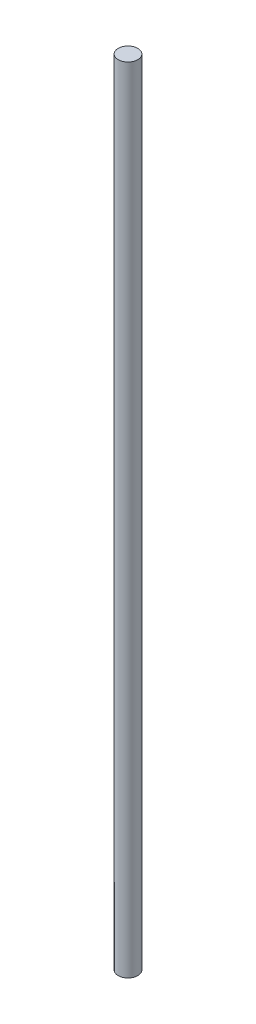
SolidWorks part; units mm, degrees
ref_plane "Plano frontal" through (0, 0, 0) normal (0, 0, 1) x (1, 0, 0)
ref_plane "Plano superior" through (0, 0, 0) normal (0, 1, 0) x (1, 0, 0)
ref_plane "Plano direito" through (0, 0, 0) normal (1, 0, 0) x (0, 0, -1)
sketch "Esboço1" plane through (0, 0, 0) normal (0, 1, 0) x (1, 0, 0)
  circle A0 centre (0, 0) radius 4
  dimension "D1" = 8
extrude "Ressalto-extrusão1" add sketch "Esboço1" along normal blind 323
